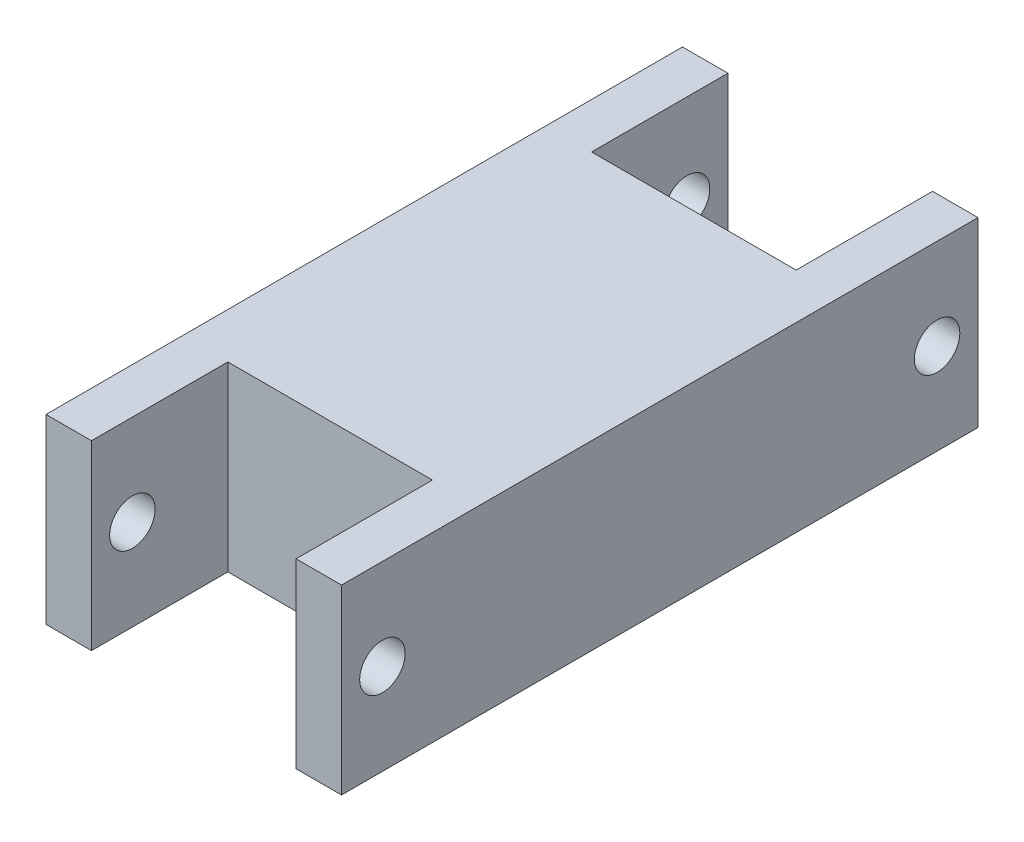
SolidWorks part; units mm, degrees
ref_plane "Front Plane" through (0, 0, 0) normal (0, 0, 1) x (1, 0, 0)
ref_plane "Top Plane" through (0, 0, 0) normal (0, 1, 0) x (1, 0, 0)
ref_plane "Right Plane" through (0, 0, 0) normal (1, 0, 0) x (0, 0, -1)
sketch "Sketch2" plane through (0, 0, 0) normal (0, 1, 0) x (1, 0, 0)
  line L0 (-22.5, 70) -> (-22.5, 40)
  line L1 (-32.5, -70) -> (-22.5, -70)
  line L2 (-32.5, -70) -> (-32.5, 70)
  line L3 (-32.5, 70) -> (-22.5, 70)
  line L4 (32.5, -70) -> (32.5, 70)
  line L5 (-32.5, -70) -> (32.5, 70) construction
  line L6 (-32.5, 70) -> (32.5, -70) construction
  line L7 (-22.5, 40) -> (22.5, 40)
  line L8 (22.5, 40) -> (22.5, 70)
  line L9 (22.5, 70) -> (32.5, 70)
  line L10 (-22.5, 0) -> (22.5, 0) construction
  line L11 (22.5, -40) -> (22.5, -70)
  line L12 (-22.5, -40) -> (22.5, -40)
  line L13 (-22.5, -70) -> (-22.5, -40)
  line L14 (22.5, -70) -> (32.5, -70)
  point P0 (0, 0)
  point P13 (0, 0)
  dimension "D1" = 65
  dimension "D2" = 140
  dimension "D3" = 10
  dimension "D4" = 10
  dimension "D5" = 30
extrude "Boss-Extrude1" add sketch "Sketch2" along normal blind 40
sketch "Sketch3" plane through (32.5, 0, 0) normal (1, 0, 0) x (0, 0, -1)
  line L0 (-70, 40) -> (-70, 0) construction
  line L1 (70, 40) -> (70, 0) construction
  circle A0 centre (-61, 20) radius 5
  circle A1 centre (61, 20) radius 5
  point P6 (0, 0)
  point P7 (-70, 20)
  point P8 (0, 0)
  point P11 (70, 20)
  dimension "D1" = 10
  dimension "D2" = 10
  dimension "D3" = 9
  dimension "D4" = 122
extrude "Cut-Extrude1" cut sketch "Sketch3" against normal up to surface (65 mm away) up to face at (-32.5, 20, 0)
